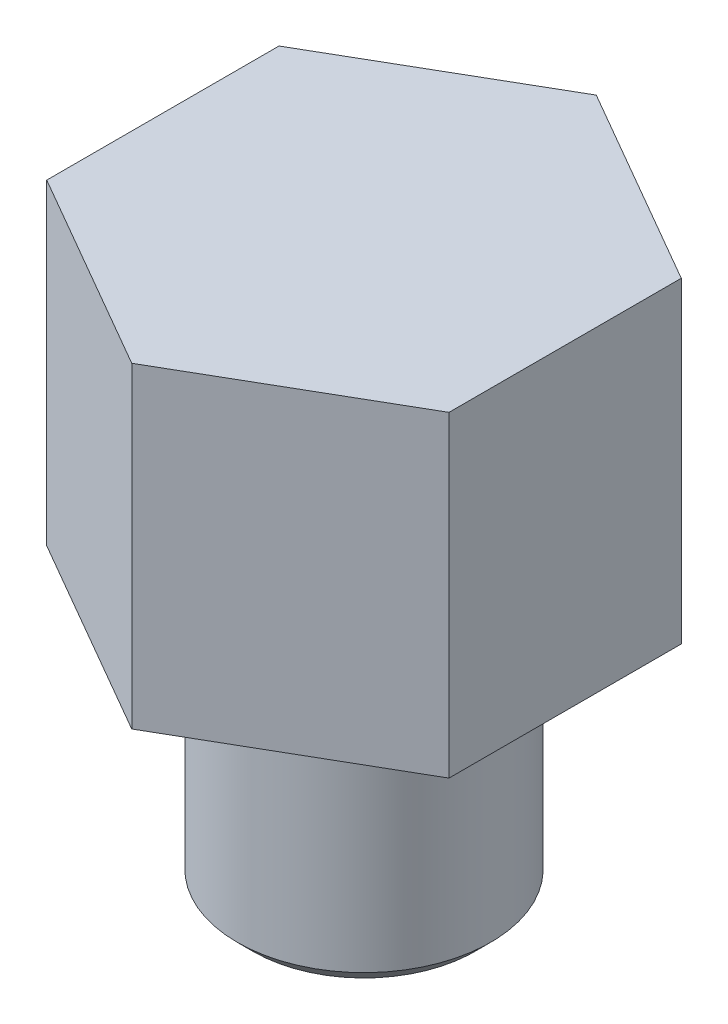
SolidWorks part; units mm, degrees
ref_plane "Front Plane" through (0, 0, 0) normal (0, 0, 1) x (1, 0, 0)
ref_plane "Top Plane" through (0, 0, 0) normal (0, 1, 0) x (1, 0, 0)
ref_plane "Right Plane" through (0, 0, 0) normal (1, 0, 0) x (0, 0, -1)
sketch "Sketch1" plane through (0, 0, 0) normal (0, 1, 0) x (1, 0, 0)
  line L1 (6.35, 3.6662) -> (0, 7.3323)
  line L2 (0, 7.3323) -> (-6.35, 3.6662)
  line L3 (-6.35, 3.6662) -> (-6.35, -3.6662)
  line L4 (-6.35, -3.6662) -> (0, -7.3323)
  line L5 (0, -7.3323) -> (6.35, -3.6662)
  line L6 (6.35, -3.6662) -> (6.35, 3.6662)
  circle A0 centre (0, 0) radius 6.35 construction
  dimension "D1" = 12.7
extrude "Boss-Extrude1" add sketch "Sketch1" along normal blind 18
sketch "Sketch2" plane through (0, 0, 0) normal (0, -1, 0) x (1, 0, 0)
  circle A0 centre (0, 0) radius 4
  circle A1 centre (0, 0) radius 11.042
  dimension "D1" = 8
extrude "Cut-Extrude1" cut sketch "Sketch2" against normal blind 8
chamfer "Chamfer1" distance 0.5 angle 45 1 edges at (0, 0, -4)
fillet "Fillet1" radius 0.5 1 edges at (0, 8, -4)
